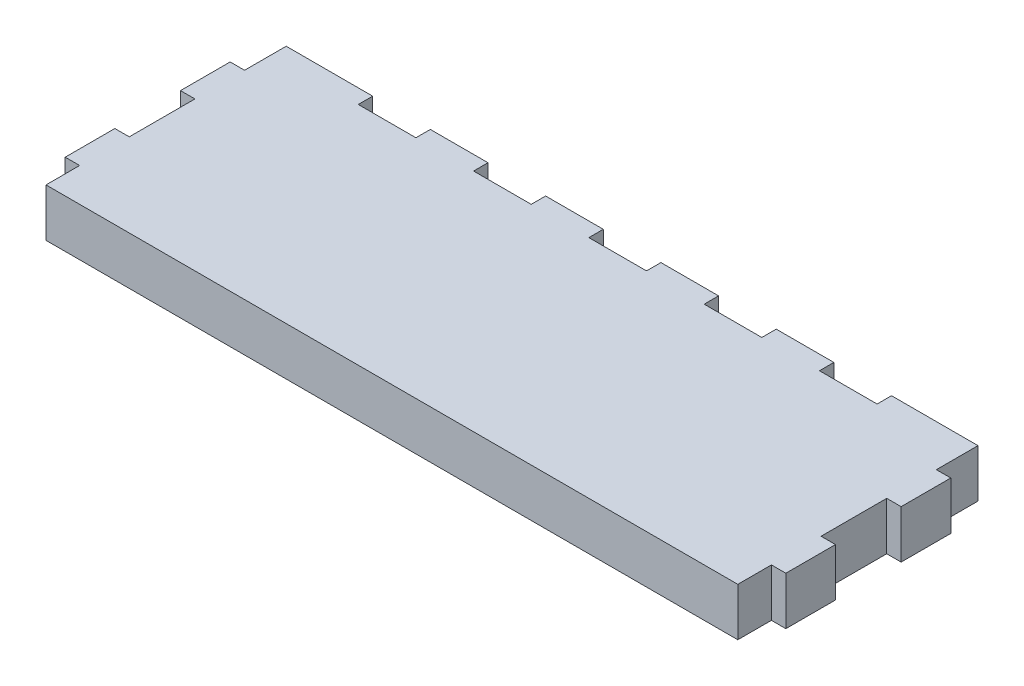
SolidWorks part; units mm, degrees
ref_plane "Front Plane" through (0, 0, 0) normal (0, 0, 1) x (1, 0, 0)
ref_plane "Top Plane" through (0, 0, 0) normal (0, 1, 0) x (1, 0, 0)
ref_plane "Right Plane" through (0, 0, 0) normal (1, 0, 0) x (0, 0, -1)
sketch "Sketch1" plane through (0, 0, 0) normal (0, 1, 0) x (1, 0, 0)
  line L149 (-32.8129, 69.7037) -> (-20.8129, 69.7037)
  line L150 (69.1871, 64.0367) -> (72.1871, 64.0367)
  line L151 (-74.8129, 72.7037) -> (-56.8129, 72.7037)
  line L152 (-74.8129, 72.7037) -> (-74.8129, 69.7037)
  line L153 (-56.8129, 72.7037) -> (-56.8129, 69.7037)
  line L154 (-56.8129, 69.7037) -> (-44.8129, 69.7037)
  line L155 (-74.8129, 69.7037) -> (-74.8129, 64.0367)
  line L156 (69.1871, 69.7037) -> (69.1871, 64.0367)
  line L157 (-77.8129, 64.0367) -> (-74.8129, 64.0367)
  line L158 (-77.8129, 64.0367) -> (-77.8129, 53.7037)
  line L159 (-77.8129, 53.7037) -> (-74.8129, 53.7037)
  line L160 (72.1871, 64.0367) -> (72.1871, 53.7037)
  line L161 (-74.8129, 53.7037) -> (-74.8129, 40.0367)
  line L162 (69.1871, 53.7037) -> (69.1871, 40.0367)
  line L163 (-77.8129, 40.0367) -> (-74.8129, 40.0367)
  line L164 (-77.8129, 40.0367) -> (-77.8129, 29.7037)
  line L165 (-77.8129, 29.7037) -> (-74.8129, 29.7037)
  line L166 (72.1871, 40.0367) -> (72.1871, 29.7037)
  line L167 (-74.8129, 29.7037) -> (-74.8129, 22.7037)
  line L168 (-74.8129, 22.7037) -> (69.1871, 22.7037)
  line L169 (69.1871, 29.7037) -> (69.1871, 22.7037)
  line L170 (-44.8129, 72.7037) -> (-32.8129, 72.7037)
  line L171 (-44.8129, 72.7037) -> (-44.8129, 69.7037)
  line L172 (-32.8129, 72.7037) -> (-32.8129, 69.7037)
  line L173 (-20.8129, 72.7037) -> (-8.8129, 72.7037)
  line L174 (-20.8129, 72.7037) -> (-20.8129, 69.7037)
  line L175 (-8.8129, 72.7037) -> (-8.8129, 69.7037)
  line L176 (3.1871, 72.7037) -> (15.1871, 72.7037)
  line L177 (3.1871, 72.7037) -> (3.1871, 69.7037)
  line L178 (15.1871, 72.7037) -> (15.1871, 69.7037)
  line L179 (27.1871, 72.7037) -> (39.1871, 72.7037)
  line L180 (27.1871, 72.7037) -> (27.1871, 69.7037)
  line L181 (39.1871, 72.7037) -> (39.1871, 69.7037)
  line L182 (51.1871, 72.7037) -> (69.1871, 72.7037)
  line L183 (51.1871, 72.7037) -> (51.1871, 69.7037)
  line L184 (69.1871, 72.7037) -> (69.1871, 69.7037)
  line L185 (69.1871, 53.7037) -> (72.1871, 53.7037)
  line L186 (69.1871, 40.0367) -> (72.1871, 40.0367)
  line L187 (69.1871, 29.7037) -> (72.1871, 29.7037)
  line L188 (-8.8129, 69.7037) -> (3.1871, 69.7037)
  line L189 (15.1871, 69.7037) -> (27.1871, 69.7037)
  line L190 (39.1871, 69.7037) -> (51.1871, 69.7037)
extrude "Boss-Extrude1" add sketch "Sketch1" along normal blind 10 separate body
